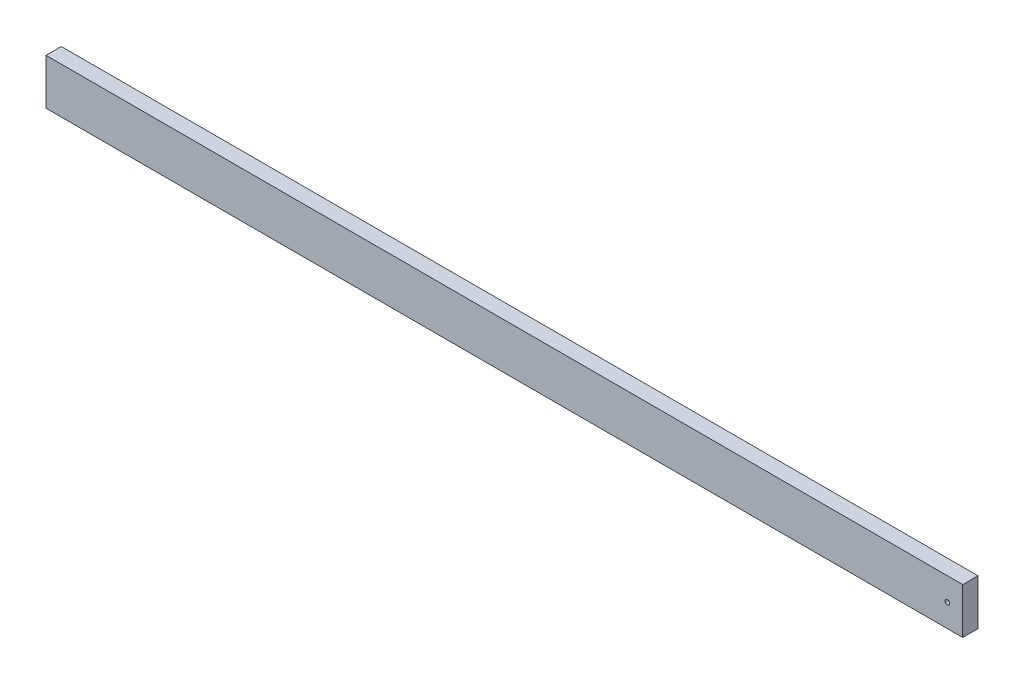
SolidWorks part; units mm, degrees
material "Oak"
ref_plane "Front Plane" through (0, 0, 0) normal (0, 0, 1) x (1, 0, 0)
ref_plane "Top Plane" through (0, 0, 0) normal (0, 1, 0) x (1, 0, 0)
ref_plane "Right Plane" through (0, 0, 0) normal (1, 0, 0) x (0, 0, -1)
sketch "Sketch1" plane through (0, 0, 0) normal (0, 0, 1) x (1, 0, 0)
  line L0 (-300, -15) -> (-300, 15)
  line L1 (-300, -15) -> (300, -15)
  line L2 (-300, 15) -> (300, 15)
  line L3 (300, -15) -> (300, 15)
  line L4 (0, 15) -> (0, -15) construction
  line L5 (-300, 0) -> (300, 0) construction
  circle A0 centre (290, 0) radius 1.5
  point P1 (0, 0)
  dimension "D3" = 3
  dimension "D1" = 600
  dimension "D2" = 30
  dimension "D4" = 10
extrude "Boss-Extrude1" add sketch "Sketch1" along normal blind 10
